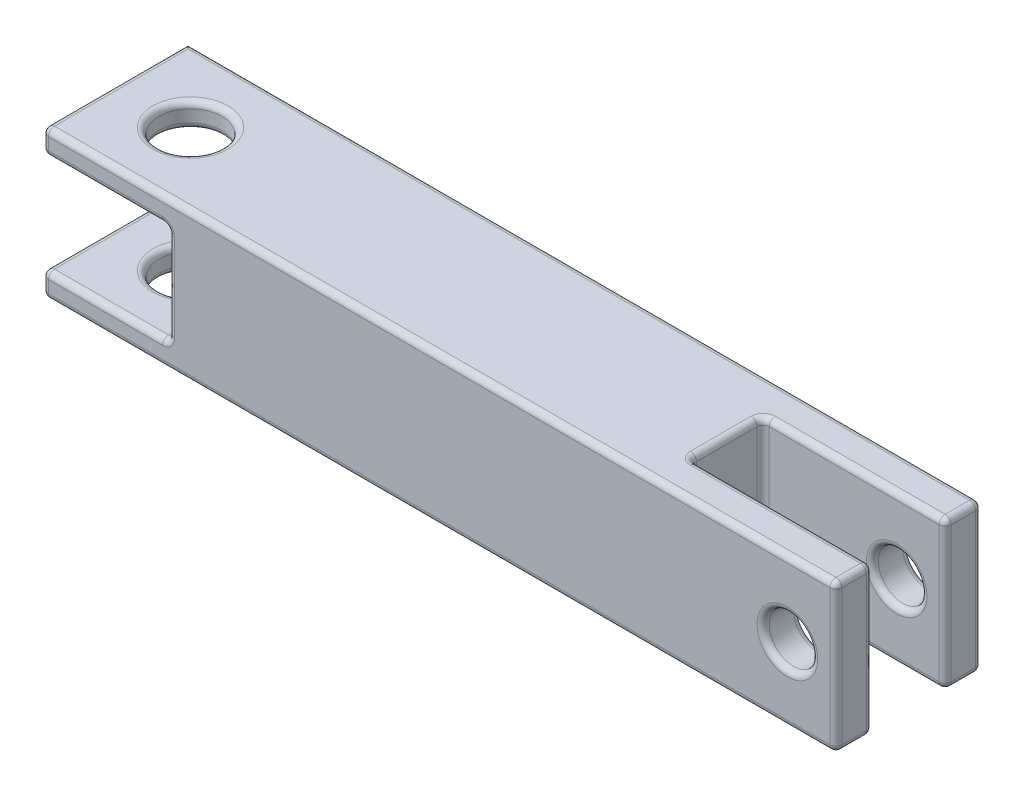
SolidWorks part; units mm, degrees
ref_plane "Front Plane" through (0, 0, 0) normal (0, 0, 1) x (1, 0, 0)
ref_plane "Top Plane" through (0, 0, 0) normal (0, 1, 0) x (1, 0, 0)
ref_plane "Right Plane" through (0, 0, 0) normal (1, 0, 0) x (0, 0, -1)
sketch "Sketch1" plane through (0, 0, 0) normal (0, 0, 1) x (1, 0, 0)
  line L0 (0, 4.1) -> (0, -4.1)
  line L1 (0, -4.1) -> (-10.4, -4.1)
  line L2 (-10.4, -4.1) -> (-10.4, -6.1)
  line L3 (-10.4, -6.1) -> (2, -6.1)
  line L9 (2, 6.1) -> (-10.4, 6.1)
  line L10 (-10.4, 6.1) -> (-10.4, 4.1)
  line L11 (-10.4, 4.1) -> (0, 4.1)
  line L13 (0, 0) -> (43.5088, 0) construction
  line L14 (2, 6.1) -> (2, -6.1)
  dimension "D1" = 10.4
  dimension "D2" = 2
  dimension "D3" = 8.2
  dimension "D4" = 2
extrude "Boss-Extrude1" add sketch "Sketch1" along normal blind 12
sketch "Sketch2" plane through (0, 6.1, 0) normal (0, 1, 0) x (1, 0, 0)
  line L0 (-4.2, 0) -> (-4.2, -12) construction
  line L1 (2, 0) -> (-10.4, 0) construction
  line L2 (2, -12) -> (-10.4, -12) construction
  line L3 (-10.4, -6) -> (24.7744, -6) construction
  line L4 (-10.4, -12) -> (-10.4, 0) construction
  circle A0 centre (-4.2, -6) radius 2.6
  point P12 (-6.3018, -6)
  dimension "D1" = 5.2
  dimension "D2" = 0
extrude "Cut-Extrude1" cut sketch "Sketch2" against normal through all both and the other way through all
sketch "Sketch3" plane through (2, 0, 0) normal (1, 0, 0) x (0, 0, -1)
  line L0 (-6, 6.1) -> (-6, -6.1) construction
  line L1 (-12, 6.1) -> (0, 6.1) construction
  line L2 (-12, -6.1) -> (0, -6.1) construction
  line L4 (-12, 6.1) -> (0, 6.1)
  line L5 (-12, 6.1) -> (-12, -6.1)
  line L6 (-12, -6.1) -> (0, -6.1)
  line L7 (0, 6.1) -> (0, -6.1)
  dimension "D1" = 12
extrude "Boss-Extrude2" add sketch "Sketch3" along normal blind 53
sketch "Sketch4" plane through (55, 0, 0) normal (1, 0, 0) x (0, 0, -1)
  line L0 (-6, 6.1) -> (-6, -6.647) construction
  line L1 (0, 6.1) -> (-12, 6.1) construction
  line L2 (-12, -6.1) -> (0, -6.1) construction
  line L3 (-9, 6.1) -> (-3, 6.1)
  line L4 (-9, 6.1) -> (-9, -6.1)
  line L5 (-9, -6.1) -> (-3, -6.1)
  line L6 (-3, 6.1) -> (-3, -6.1)
  dimension "D1" = 6
extrude "Cut-Extrude2" cut sketch "Sketch4" against normal blind 15 and the other way through all
sketch "Sketch5" plane through (0, 0, 12) normal (0, 0, 1) x (1, 0, 0)
  line L0 (55, 0) -> (0, 0) construction
  line L1 (55, 6.1) -> (55, -6.1) construction
  line L2 (51, 6.1) -> (51, -6.1) construction
  line L3 (55, 6.1) -> (-10.4, 6.1) construction
  line L4 (55, -6.1) -> (-10.4, -6.1) construction
  circle A0 centre (51, 0) radius 2
  dimension "D2" = 4
  dimension "D1" = 4
extrude "Cut-Extrude3" cut sketch "Sketch5" against normal through all
fillet "Fillet1" radius 0.5 42 edges at (-10.4, 5.1, 12) (-10.4, -5.1, 12) (-10.4, 4.1, 6) (-5.2, 4.1, 12) (-5.2, 4.1, 0) (-6.8, 4.1, 6) (0, 4.1, 6) (0, 0, 12) (0, 0, 0) (0, -4.1, 6) (-5.2, -4.1, 12) (-10.4, -4.1, 6) (-5.2, -4.1, 0) (-1.6, -4.1, 6) (40, -6.1, 6) (47.5, -6.1, 3) (55, -6.1, 1.5) (22.3, -6.1, 0) (-10.4, -6.1, 6) (22.3, -6.1, 12) (55, -6.1, 10.5) (47.5, -6.1, 9) (-6.8, -6.1, 6) (55, 6.1, 10.5) (22.3, 6.1, 12) (-10.4, 6.1, 6) (22.3, 6.1, 0) (55, 6.1, 1.5) (47.5, 6.1, 3) (40, 6.1, 6) (47.5, 6.1, 9) (-1.6, 6.1, 6) (40, 0, 3) (40, 0, 9) (55, 0, 12) (55, 0, 9) (55, 0, 0) (55, 0, 3) (51, 2, 9) (53, 0, 12) (51, -2, 3) (53, 0, 0)
